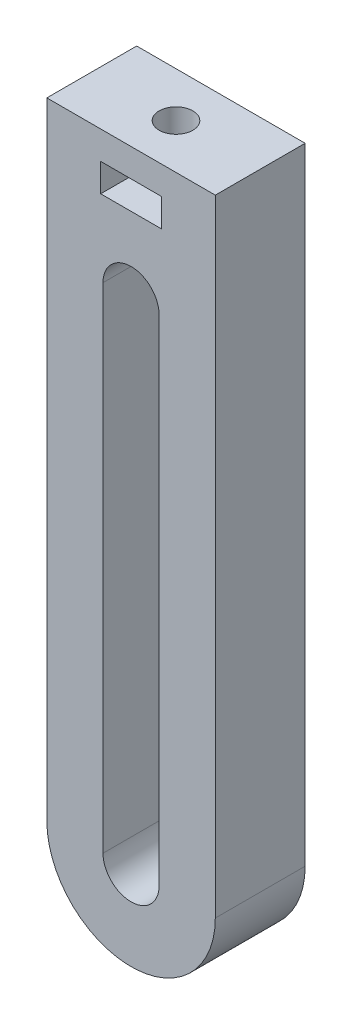
SolidWorks part; units mm, degrees
material "PLA Density Only"
ref_plane "Front Plane" through (0, 0, 0) normal (0, 0, 1) x (1, 0, 0)
ref_plane "Top Plane" through (0, 0, 0) normal (0, 1, 0) x (1, 0, 0)
ref_plane "Right Plane" through (0, 0, 0) normal (1, 0, 0) x (0, 0, -1)
sketch "Sketch1" plane through (0, 0, 0) normal (0, 0, 1) x (1, 0, 0)
  line L0 (0, 22) -> (0, -22) construction
  line L1 (2.5, 22) -> (2.5, -22)
  line L2 (-2.5, 22) -> (-2.5, -22)
  line L7 (-7.5, 33.75) -> (7.5, 33.75)
  line L8 (-7.5, 33.75) -> (-7.5, -22)
  line L10 (7.5, -22) -> (7.5, 33.75)
  arc A0 (2.5, 22) -> (-2.5, 22) centre (0, 22) ccw
  arc A1 (-2.5, -22) -> (2.5, -22) centre (0, -22) ccw
  arc A4 (7.5, -22) -> (-7.5, -22) centre (0, -22) cw
  point P2 (0, 0)
  point P11 (0, 33.75)
  dimension "D3" = 2.5
  dimension "D1" = 11.75
  dimension "D2" = 44
  dimension "D4" = 15
extrude "Boss-Extrude1" add sketch "Sketch1" along normal blind 8
sketch "Sketch3" plane through (0, 33.75, 0) normal (0, 1, 0) x (1, 0, 0)
  line L0 (7.5, 0) -> (-7.5, 0) construction
  line L1 (0, -7.1235) -> (2.705, -5.5617)
  line L2 (2.705, -5.5617) -> (2.705, -2.4383)
  line L3 (2.705, -2.4383) -> (0, -0.8765)
  line L4 (0, -0.8765) -> (-2.705, -2.4383)
  line L5 (-2.705, -2.4383) -> (-2.705, -5.5617)
  line L6 (-2.705, -5.5617) -> (0, -7.1235)
  circle A0 centre (0, -4) radius 2.705 construction
  dimension "D1" = 5.41
  dimension "D2" = 4
extrude "Cut-Extrude2" cut sketch "Sketch3" against normal blind 2.5 from offset 2.5 offset against normal yes
sketch "Sketch4" plane through (0, 0, 8) normal (0, 0, 1) x (1, 0, 0)
  line L1 (-2.705, 31.25) -> (2.705, 31.25)
  line L2 (-2.705, 31.25) -> (-2.705, 28.75)
  line L3 (-2.705, 28.75) -> (2.705, 28.75)
  line L4 (2.705, 31.25) -> (2.705, 28.75)
  line L5 (-2.705, 31.25) -> (2.705, 28.75) construction
  line L6 (-2.705, 28.75) -> (2.705, 31.25) construction
  line L7 (7.5, 33.75) -> (-7.5, 33.75) construction
  point P0 (0, 30)
  dimension "D1" = 2.5
  dimension "D2" = 5.41
  dimension "D3" = 2.5
extrude "Cut-Extrude3" cut sketch "Sketch4" against normal blind 4
sketch "Sketch5" plane through (0, 33.75, 0) normal (0, 1, 0) x (1, 0, 0)
  line L0 (7.5, 0) -> (-7.5, 0) construction
  circle A0 centre (0, -4) radius 1.5
  dimension "D1" = 3
  dimension "D2" = 4
extrude "Cut-Extrude4" cut sketch "Sketch5" against normal up to surface (9.25 mm away)
